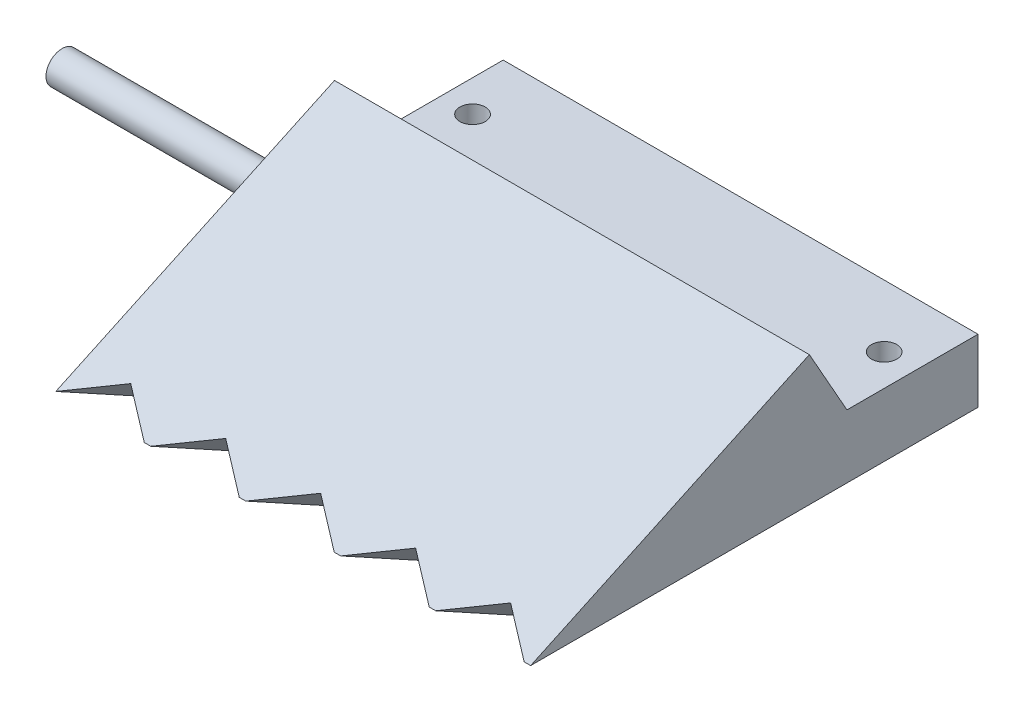
SolidWorks part; units mm, degrees
ref_plane "Front Plane" through (0, 0, 0) normal (0, 0, 1) x (1, 0, 0)
ref_plane "Top Plane" through (0, 0, 0) normal (0, 1, 0) x (1, 0, 0)
ref_plane "Right Plane" through (0, 0, 0) normal (1, 0, 0) x (0, 0, -1)
sketch "Sketch1" plane through (0, 0, 0) normal (1, 0, 0) x (0, 0, -1)
  line L0 (-35.4476, 4.1732) -> (35.2065, 4.1732)
  line L1 (35.2065, 4.1732) -> (35.2065, 14.1732)
  line L2 (35.2065, 14.1732) -> (14.5119, 14.1732)
  line L3 (14.5119, 14.1732) -> (8.5711, 24.6994)
  line L4 (8.5711, 24.6994) -> (-35.4476, 4.1732)
  dimension "D1" = 25
  dimension "D2" = 10
  dimension "D3" = 49.9595
extrude "Boss-Extrude1" add sketch "Sketch1" along normal blind 75
sketch "Sketch2" plane through (0, 14.1732, 0) normal (0, 1, 0) x (1, 0, 0)
  line L0 (0, -11.2894) -> (0, 11.2894) construction
  circle A0 centre (5, 25.3746) radius 2
  circle A1 centre (70, 25.3862) radius 2
  dimension "D1" = 4
  dimension "D2" = 4
  dimension "D3" = 65
  dimension "D4" = 5
extrude "Cut-Extrude1" cut sketch "Sketch2" against normal blind 10
sketch "Sketch3" plane through (0, 0, 0) normal (-1, 0, 0) x (0, 0, 1)
  circle A0 centre (-5.5476, 8.0335) radius 2.543
sketch "Sketch4" plane through (0, 17.0051, 7.9296) normal (0, 0.9063, 0.4226) x (1, 0, 0)
  line L0 (0, -30.3628) -> (7.0659, -25.1031)
  line L1 (0, -11.2894) -> (0, 11.2894) construction
  line L2 (75, -30.3628) -> (0, -30.3628) construction
  line L3 (7.0659, -25.1031) -> (13.9766, -30.3628)
  line L4 (22.0659, -25.1031) -> (28.9766, -30.3628)
  line L5 (15, -30.3628) -> (22.0659, -25.1031)
  line L6 (37.0659, -25.1031) -> (43.9766, -30.3628)
  line L7 (30, -30.3628) -> (37.0659, -25.1031)
  line L8 (52.0659, -25.1031) -> (58.9766, -30.3628)
  line L9 (45, -30.3628) -> (52.0659, -25.1031)
  line L10 (67.0659, -25.1031) -> (73.9766, -30.3628)
  line L11 (60, -30.3628) -> (67.0659, -25.1031)
  line L12 (13.9766, -30.3628) -> (0, -30.3628)
  line L13 (15, -30.3628) -> (28.9766, -30.3628)
  line L14 (43.9766, -30.3628) -> (30, -30.3628)
  line L15 (45, -30.3628) -> (58.9766, -30.3628)
  line L16 (73.9766, -30.3628) -> (60, -30.3628)
  dimension "D1" = 5
extrude "Cut-Extrude2" cut sketch "Sketch4" against normal blind 10
chamfer "Chamfer1" distance 2 angle 45 2 edges at (70, 4.1732, -23.3862) (5, 4.1732, -23.3746)
extrude "Boss-Extrude2" add sketch "Sketch3" along normal blind 40
